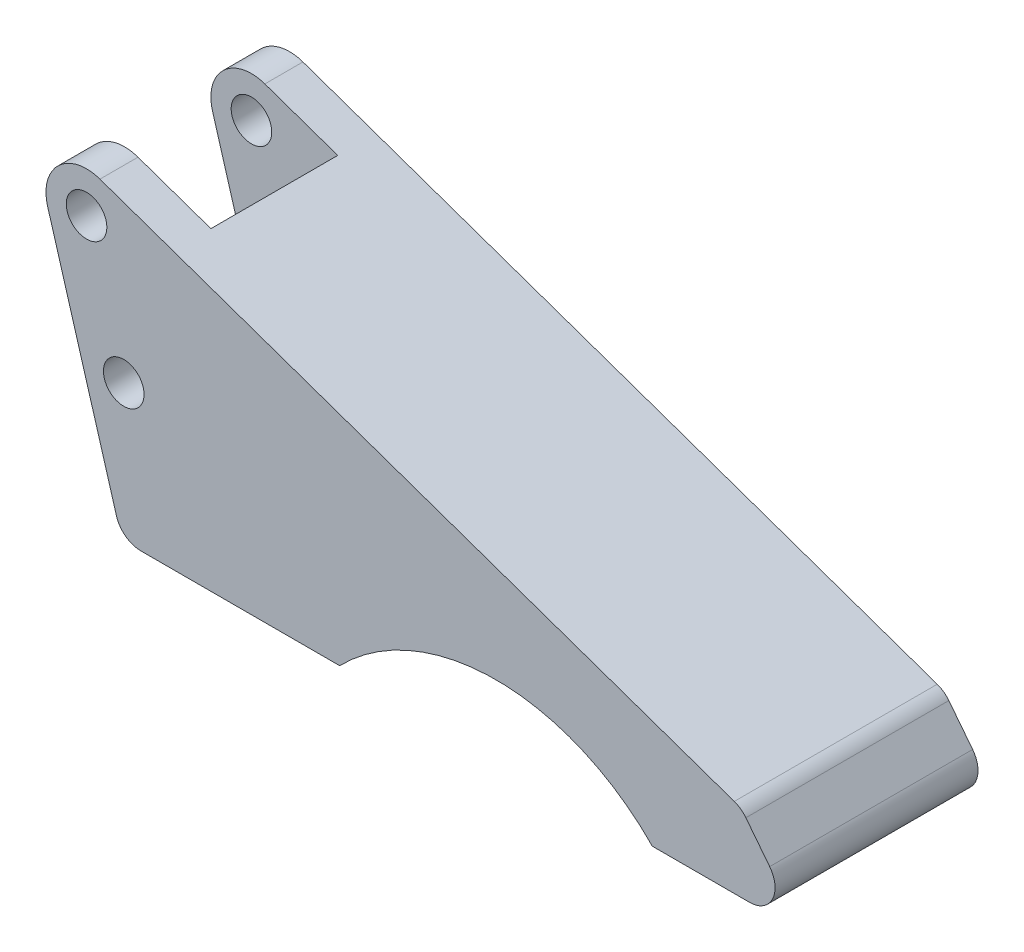
SolidWorks part; units mm, degrees
ref_plane "Front Plane" through (0, 0, 0) normal (0, 0, 1) x (1, 0, 0)
ref_plane "Top Plane" through (0, 0, 0) normal (0, 1, 0) x (1, 0, 0)
ref_plane "Right Plane" through (0, 0, 0) normal (1, 0, 0) x (0, 0, -1)
sketch "Sketch1" plane through (0, 0, 0) normal (0, 0, 1) x (1, 0, 0)
  line L5 (0, -5) -> (39.1942, -5)
  line L6 (100.8058, -5) -> (120, -5)
  line L7 (123.9398, 3.0786) -> (119.2513, 9.0786)
  line L8 (116.9615, 10.7199) -> (-8.05, 54.4218)
  line L9 (-18.3635, 44.6078) -> (-4.7959, -1.4139)
  arc A5 (-4.7959, -1.4139) -> (0, -5) centre (0, 0) ccw
  arc A6 (39.1942, -5) -> (100.8058, -5) centre (70, -35) cw
  arc A7 (120, -5) -> (123.9398, 3.0786) centre (120, 0) ccw
  arc A9 (-8.05, 54.4218) -> (-18.3635, 44.6078) centre (-10.69, 46.87) ccw
  circle A10 centre (-3.36, 22) radius 4
  circle A11 centre (-10.69, 46.87) radius 4
  arc A12 (119.2513, 9.0786) -> (116.9615, 10.7199) centre (115.3115, 6) ccw
  dimension "D2" = 70
  dimension "D3" = 30
  dimension "D4" = 5
  dimension "D5" = 43
  dimension "D6" = 5
  dimension "D7" = 8
  dimension "D8" = 5
  dimension "D13" = 8
  dimension "D9" = 6
  dimension "D10" = 27
  dimension "D11" = 24.87
  dimension "D12" = 7.33
  dimension "D14" = 3.36
  dimension "D15" = 1.65
  dimension "D16" = 120
extrude "Boss-Extrude1" add sketch "Sketch1" along normal mid plane 40
sketch "Sketch3" plane through (0, 0, 0) normal (0, 1, 0) x (1, 0, 0)
  line L0 (-18.69, 20) -> (-18.69, -20) construction
  line L1 (6.31, -12.5) -> (-18.69, -12.5)
  line L2 (6.31, -12.5) -> (6.31, 12.5)
  line L3 (6.31, 12.5) -> (-18.69, 12.5)
  line L4 (-18.69, -12.5) -> (-18.69, 12.5)
  line L5 (6.31, -12.5) -> (-18.69, 12.5) construction
  line L6 (6.31, 12.5) -> (-18.69, -12.5) construction
  point P0 (-6.19, 0)
  dimension "D1" = 25
  dimension "D2" = 25
extrude "Cut-Extrude1" cut sketch "Sketch3" against normal through all both and the other way through all
